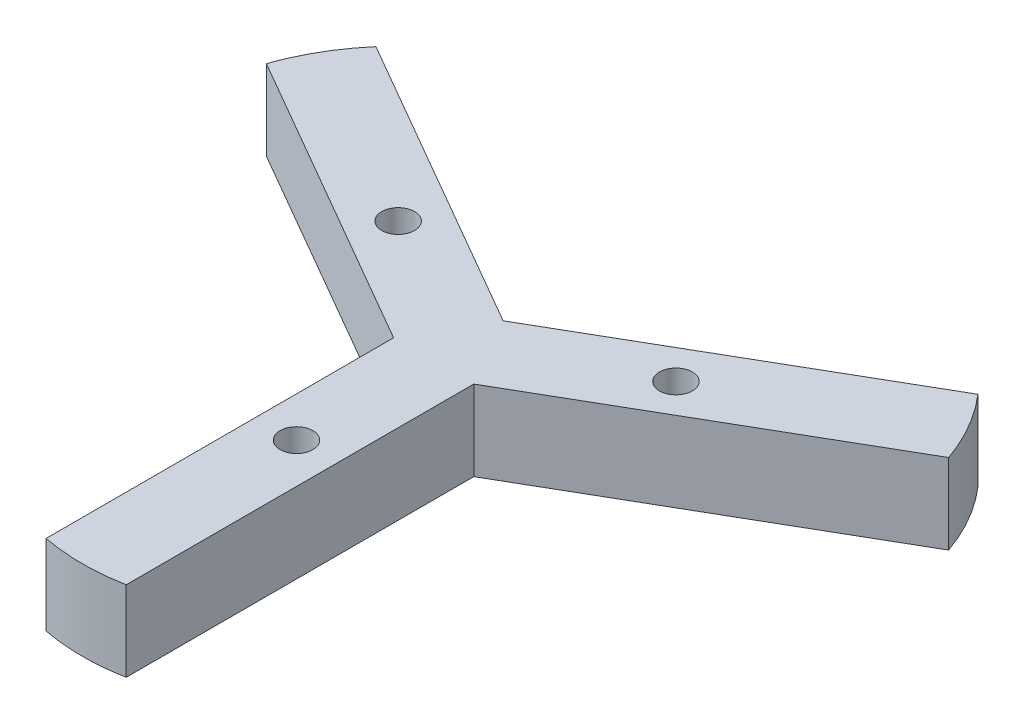
SolidWorks part; units mm, degrees
ref_plane "Front Plane" through (0, 0, 0) normal (0, 0, 1) x (1, 0, 0)
ref_plane "Top Plane" through (0, 0, 0) normal (0, 1, 0) x (1, 0, 0)
ref_plane "Right Plane" through (0, 0, 0) normal (1, 0, 0) x (0, 0, -1)
sketch "Sketch1" plane through (0, 0, 0) normal (0, 1, 0) x (1, 0, 0)
  line L0 (0, 0) -> (0, -25.4) construction
  line L3 (6.35, -3.6662) -> (6.35, -58.7188)
  line L6 (-6.35, -3.6662) -> (-6.35, -58.7188)
  line L12 (0, 7.3323) -> (-47.677, 34.8587)
  line L13 (-6.35, -3.6662) -> (-54.027, 23.8601)
  line L14 (6.35, -3.6662) -> (54.027, 23.8601)
  line L15 (0, 7.3323) -> (47.677, 34.8587)
  arc A12 (-6.35, -58.7188) -> (6.35, -58.7188) centre (0, -25.4) ccw
  circle A13 centre (0, -25.4) radius 2.6035
  arc A14 (-47.677, 34.8587) -> (-54.027, 23.8601) centre (-21.997, 12.7) ccw
  circle A15 centre (-21.997, 12.7) radius 2.6035
  arc A16 (54.027, 23.8601) -> (47.677, 34.8587) centre (21.997, 12.7) ccw
  circle A17 centre (21.997, 12.7) radius 2.6035
  point P3 (0, -29.3594)
  point P27 (0, 0)
  dimension "D1" = 12.7
  dimension "D3" = 3
  dimension "D2" = 5.207
  dimension "D4" = 25.4
extrude "Boss-Extrude1" add sketch "Sketch1" along normal blind 12.7
